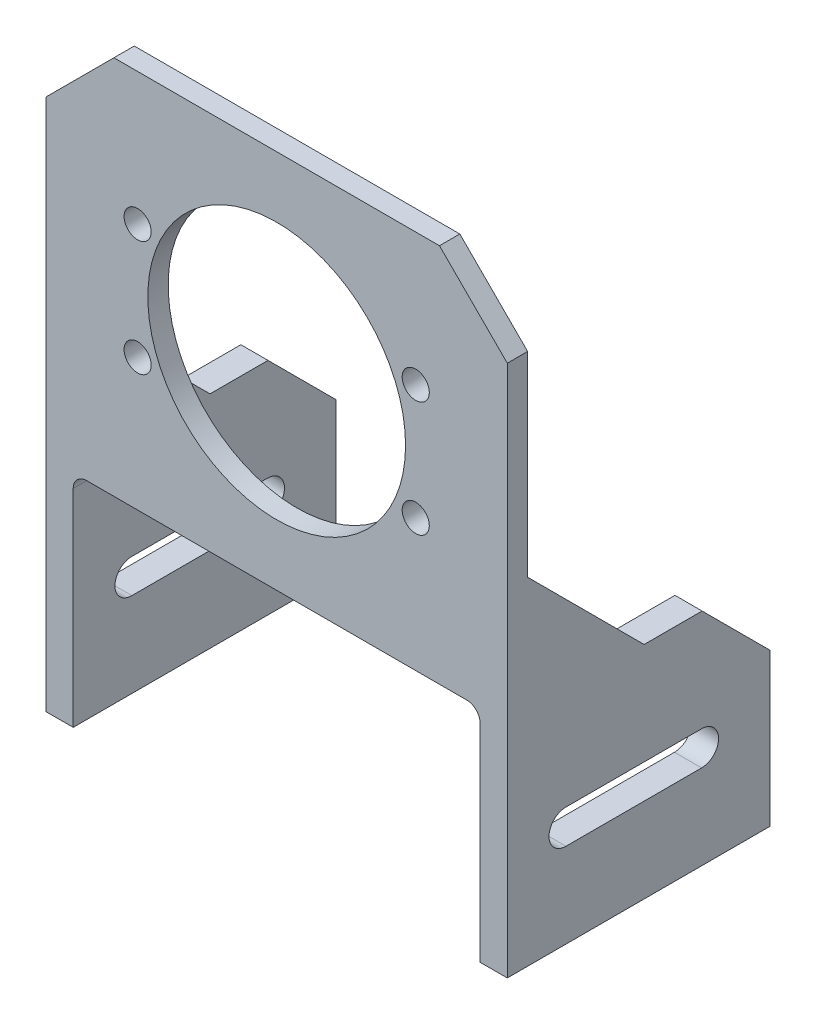
SolidWorks part; units mm, degrees
ref_plane "前视基准面" through (0, 0, 0) normal (0, 0, 1) x (1, 0, 0)
ref_plane "上视基准面" through (0, 0, 0) normal (0, 1, 0) x (1, 0, 0)
ref_plane "右视基准面" through (0, 0, 0) normal (1, 0, 0) x (0, 0, -1)
other "Configuration Table"
sketch "草图1" plane through (0, 0, 0) normal (0, 0, 1) x (1, 0, 0)
  line L1 (-24, 28) -> (24, 28)
  line L2 (0, 21.7716) -> (0, 13.4995) construction
  line L3 (-34, 18) -> (-24, 28)
  line L8 (34, 18) -> (24, 28)
  line L10 (-34, -28) -> (34, -28)
  line L11 (-34, -28) -> (-34, 18)
  line L13 (34, -28) -> (34, 18)
  line L14 (-34, -28) -> (23.8122, 19.6101) construction
  line L17 (-23.5445, 22.3514) -> (34, -28) construction
  arc A6 (-15.1691, 11.441) -> (-15.1691, -11.441) centre (0, 0) ccw construction
  arc A14 (-15.1691, 11.441) -> (-15.1691, -11.441) centre (0, 0) ccw
  circle A16 centre (20.5, -8.5) radius 2 construction
  circle A17 centre (20.5, 8.5) radius 2 construction
  circle A18 centre (-20.5, -8.5) radius 2 construction
  circle A19 centre (-20.5, 8.5) radius 2 construction
  circle A20 centre (20.5, -8.5) radius 2
  circle A21 centre (20.5, 8.5) radius 2
  circle A22 centre (-20.5, -8.5) radius 2
  circle A23 centre (-20.5, 8.5) radius 2
  circle A25 centre (0, 0) radius 19
  dimension "D3" = 10
  dimension "D1" = 68
  dimension "D2" = 10
extrude "凸台-拉伸1" add sketch "草图1" along normal blind 3
sketch "草图3" plane through (34, 0, 0) normal (1, 0, 0) x (0, 0, -1)
  line L0 (-3, -28) -> (-3, -60.5)
  line L1 (-3, -60.5) -> (35.7207, -60.5)
  line L2 (35.7207, -60.5) -> (35.7207, -38)
  line L3 (35.7207, -38) -> (25.7207, -28)
  line L4 (25.7207, -28) -> (-3, -28)
  line L5 (-11.3318, -45.5) -> (50.8972, -45.5) construction
  line L6 (5.647, -45.5) -> (25.647, -45.5) construction
  line L7 (5.647, -43) -> (25.647, -43)
  line L8 (5.647, -48) -> (25.647, -48)
  arc A0 (5.647, -43) -> (5.647, -48) centre (5.647, -45.5) ccw
  arc A1 (25.647, -48) -> (25.647, -43) centre (25.647, -45.5) ccw
  point P10 (15.647, -45.5)
  dimension "D1" = 32.5
  dimension "D2" = 10
  dimension "D3" = 10
  dimension "D4" = 15
  dimension "D5" = 5
  dimension "D6" = 20
extrude "凸台-拉伸2" add sketch "草图3" against normal blind 4
fillet "圆角3" radius 2 1 edges at (32, -28, 0)
fillet "圆角4" radius 2 2 edges at (30, -28, 1.5) (30, -27, 0)
mirror "镜向1" about plane through (0, 0, 0) normal (1, 0, 0) of "圆角4", "圆角3", "凸台-拉伸2"
sketch "草图4" plane through (34, 0, 0) normal (1, 0, 0) x (0, 0, -1)
  line L0 (0, -10.8269) -> (17.1731, -28)
  line L1 (0, -26) -> (0, 18) construction
  line L2 (25.7207, -28) -> (2, -28) construction
  dimension "D1" = 45
rib "筋1" sketch "草图4" sketch "草图4" thickness 4 extrusion direction parallel to sketch draft on no parameters "D1"=4
mirror "镜向2" about plane through (0, 0, 0) normal (1, 0, 0) of "筋1"
